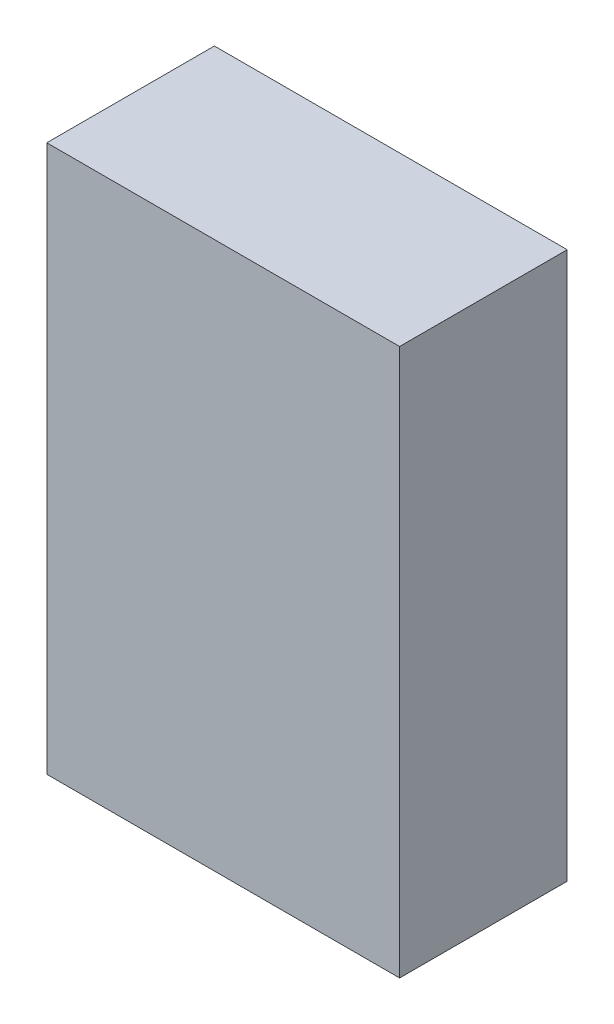
SolidWorks part; units mm, degrees
ref_plane "Front Plane" through (0, 0, 0) normal (0, 0, 1) x (1, 0, 0)
ref_plane "Top Plane" through (0, 0, 0) normal (0, 1, 0) x (1, 0, 0)
ref_plane "Right Plane" through (0, 0, 0) normal (1, 0, 0) x (0, 0, -1)
sketch "Sketch1" plane through (0, 0, 0) normal (0, 0, 1) x (1, 0, 0)
  line L1 (-10, -15.5) -> (10, -15.5)
  line L2 (-10, -15.5) -> (-10, 15.5)
  line L3 (-10, 15.5) -> (10, 15.5)
  line L4 (10, -15.5) -> (10, 15.5)
  line L5 (-10, -15.5) -> (10, 15.5) construction
  line L6 (-10, 15.5) -> (10, -15.5) construction
  point P0 (0, 0)
  dimension "D1" = 31
  dimension "D2" = 20
extrude "Boss-Extrude1" add sketch "Sketch1" along normal blind 9.5
